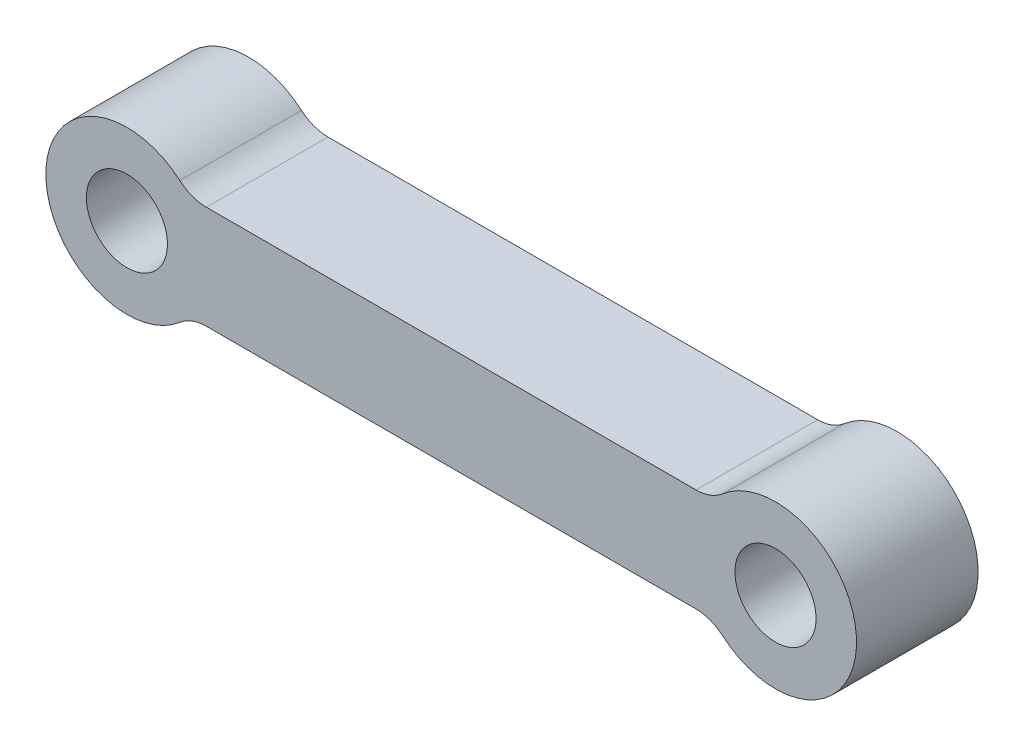
SolidWorks part; units mm, degrees
material "Pine"
ref_plane "Front Plane" through (0, 0, 0) normal (0, 0, 1) x (1, 0, 0)
ref_plane "Top Plane" through (0, 0, 0) normal (0, 1, 0) x (1, 0, 0)
ref_plane "Right Plane" through (0, 0, 0) normal (1, 0, 0) x (0, 0, -1)
sketch "Sketch1" plane through (0, 0, 0) normal (0, 0, 1) x (1, 0, 0)
  line L0 (0, 0) -> (32, 0) construction
  line L1 (3.0873, 2.5434) -> (28.9127, 2.5434)
  line L2 (3.0873, -2.5434) -> (28.9127, -2.5434)
  line L3 (16, 0) -> (16, 30) construction
  line L4 (16, 0) -> (16, -30) construction
  arc A0 (0, 4) -> (0, -4) centre (0, 0) ccw
  arc A1 (32, -4) -> (32, 4) centre (32, 0) ccw
  circle A2 centre (0, 0) radius 2
  circle A3 centre (32, 0) radius 2
  arc A4 (28.9127, -2.5434) -> (28.9127, 2.5434) centre (32, 0) ccw
  arc A5 (3.0873, 2.5434) -> (3.0873, -2.5434) centre (0, 0) ccw
  point P3 (7.5, 0)
  dimension "D1" = 4
  dimension "D4" = 16
  dimension "D2" = 4
  dimension "D3" = 32
  dimension "D5" = 16
extrude "Boss-Extrude1" add sketch "Sketch1" along normal blind 6 contours L1 A5 A0 L2 A4 A1 A3 A2
fillet "Fillet1" radius 2 4 edges at (28.9127, 2.5434, 3) (3.0873, 2.5434, 3) (28.9127, -2.5434, 3) (3.0873, -2.5434, 3)
